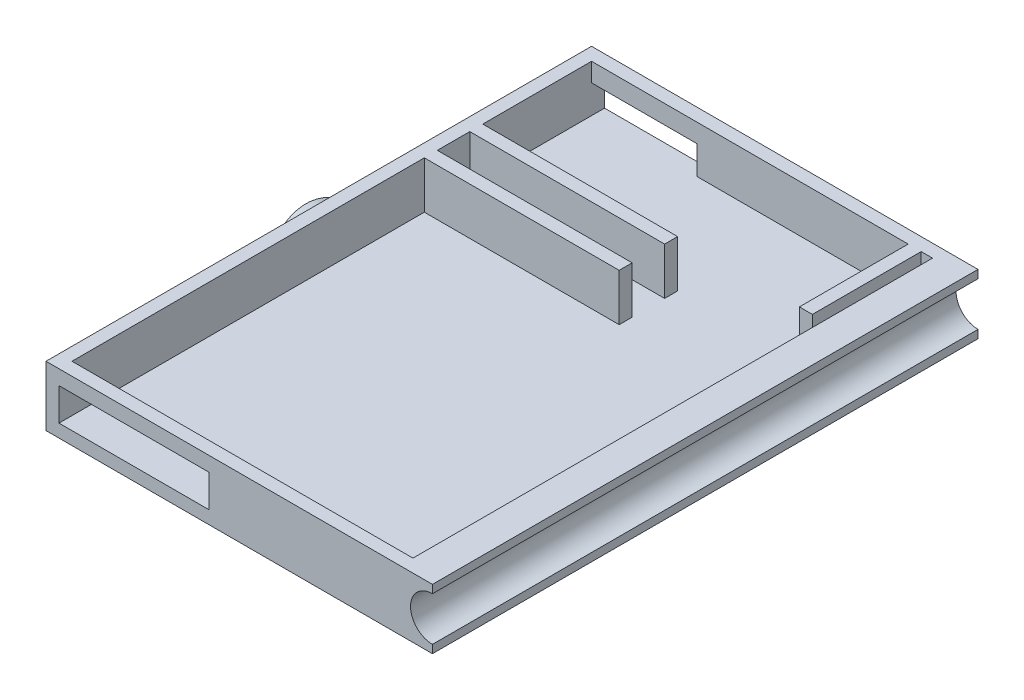
SolidWorks part; units mm, degrees
ref_plane "Front Plane" through (0, 0, 0) normal (0, 0, 1) x (1, 0, 0)
ref_plane "Top Plane" through (0, 0, 0) normal (0, 1, 0) x (1, 0, 0)
ref_plane "Right Plane" through (0, 0, 0) normal (1, 0, 0) x (0, 0, -1)
sketch "Sketch2" plane through (0, 0, 0) normal (0, 1, 0) x (1, 0, 0)
  line L1 (0, 0) -> (42, 0)
  line L2 (0, 0) -> (0, -64)
  line L3 (0, -64) -> (42, -64)
  line L4 (42, 0) -> (42, -64)
  dimension "D1" = 42
  dimension "D2" = 64
extrude "Boss-Extrude1" add sketch "Sketch2" along normal blind 1.6
sketch "Sketch4" plane through (0, 0, 0) normal (0, 1, 0) x (1, 0, 0)
  line L0 (0, 0) -> (0, -64) construction
  line L1 (-1.6, 1.6) -> (46, 1.6)
  line L2 (-1.6, 1.6) -> (-1.6, -65.6)
  line L3 (-1.6, -65.6) -> (46, -65.6)
  line L4 (46, 1.6) -> (46, -65.6)
  line L5 (42, 0) -> (0, 0) construction
  line L6 (42, -64) -> (42, 0) construction
  line L7 (0, -64) -> (42, -64) construction
  line L9 (0, 0) -> (42, 0)
  line L10 (0, 0) -> (0, -64)
  line L11 (0, -64) -> (42, -64)
  line L12 (42, 0) -> (42, -64)
  dimension "D1" = 1.6
  dimension "D2" = 1.6
  dimension "D3" = 4
  dimension "D4" = 1.6
extrude "Boss-Extrude2" add sketch "Sketch4" along normal blind 6.6
sketch "Sketch6" plane through (-1.6, 0, 0) normal (-1, 0, 0) x (0, 0, 1)
  line L0 (-1.6, 0) -> (65.6, 0) construction
  line L1 (25.4, 0) -> (38.6, 0)
  arc A0 (38.6, 0) -> (25.4, 0) centre (32, 0) ccw
extrude "Boss-Extrude3" add sketch "Sketch6" along normal blind 1.6
sketch "Sketch7" plane through (0, 0, 0) normal (0, 0, 1) x (1, 0, 0)
  line L0 (-3.2, 3.3) -> (-3.2, 0)
  line L1 (-3.2, 6.6) -> (-3.2, 0) construction
  line L2 (-3.2, 6.6) -> (-3.2, 3.3)
  line L3 (-3.2, 4.95) -> (-2.7, 4.95)
  line L4 (-2.7, 4.95) -> (-3.2, 6.6)
  line L5 (-3.2, 3.3) -> (-2.7, 3.3)
  line L6 (-2.7, 3.3) -> (-3.2, 4.95)
  line L7 (-3.2, 1.65) -> (-2.7, 1.65)
  line L8 (-2.7, 1.65) -> (-3.2, 3.3)
  line L9 (-3.2, 0) -> (-2.7, 0)
  line L10 (-3.2, 0) -> (-1.6, 0) construction
  line L11 (-2.7, 0) -> (-3.2, 1.65)
  dimension "D1" = 0.5
extrude "Cut-Extrude2" cut sketch "Sketch7" along normal blind 53.6 contours L3 L4 L2 | L5 L6 L2 | L7 L8 L0 | L9 L11 L0
sketch "Sketch12" plane through (0, 0, 64) normal (0, 0, -1) x (-1, 0, 0)
  line L1 (0, 1.6) -> (-18.5, 1.6)
  line L2 (0, 1.6) -> (0, 5.6)
  line L3 (0, 5.6) -> (-18.5, 5.6)
  line L4 (-18.5, 1.6) -> (-18.5, 5.6)
  dimension "D1" = 4
  dimension "D2" = 18.5
extrude "Cut-Extrude5" cut sketch "Sketch12" against normal blind 4.5
sketch "Sketch14" plane through (0, 1.6, 0) normal (0, 1, 0) x (1, 0, 0)
  line L0 (0, 0) -> (0, -65.6) construction
  line L1 (0, -20.6) -> (24, -20.6)
  line L2 (0, -20.6) -> (0, -13.4)
  line L3 (0, -13.4) -> (24, -13.4)
  line L4 (24, -20.6) -> (24, -13.4)
  line L6 (-1.6, -65.6) -> (46, -65.6) construction
  line L7 (42, 0) -> (0, 0) construction
  dimension "D1" = 45
  dimension "D2" = 13.4
  dimension "D3" = 24
extrude "Boss-Extrude6" add sketch "Sketch14" along normal blind 5
sketch "Sketch21" plane through (0, 6.6, 0) normal (0, 1, 0) x (1, 0, 0)
  line L0 (0, -13.4) -> (0, 0)
  line L1 (-1.6, 1.6) -> (46, 1.6)
  line L2 (-1.6, 1.6) -> (-1.6, -65.6)
  line L3 (-1.6, -65.6) -> (46, -65.6)
  line L4 (46, 1.6) -> (46, -65.6)
  line L5 (42, -64) -> (0, -64)
  line L6 (42, -64) -> (42, 0)
  line L7 (42, 0) -> (0, 0)
  line L8 (0, -64) -> (0, -20.6)
  line L9 (0, -13.4) -> (24, -13.4)
  line L11 (0, -20.6) -> (24, -20.6)
  line L12 (24, -13.4) -> (24, -20.6)
extrude "Boss-Extrude8" add sketch "Sketch21" along normal blind 0.8
sketch "Sketch22" plane through (0, 0, 0) normal (0, 0, 1) x (1, 0, 0)
  line L1 (0, 1.6) -> (13, 1.6)
  line L2 (0, 1.6) -> (0, 5.1)
  line L3 (0, 5.1) -> (13, 5.1)
  line L4 (13, 1.6) -> (13, 5.1)
  dimension "D1" = 13
  dimension "D2" = 3.5
extrude "Cut-Extrude6" cut sketch "Sketch22" against normal blind 10.8
sketch "Sketch26" plane through (0, 7.4, 0) normal (0, 1, 0) x (1, 0, 0)
  line L0 (24, -13.4) -> (24, -20.6) construction
  line L1 (24, -15) -> (0, -15)
  line L2 (24, -15) -> (24, -19)
  line L3 (24, -19) -> (0, -19)
  line L4 (0, -15) -> (0, -19)
  line L5 (24, -13.4) -> (0, -13.4) construction
  line L6 (24, -20.6) -> (0, -20.6) construction
  line L7 (-1.6, 1.6) -> (-1.6, -65.6) construction
  dimension "D1" = 1.6
  dimension "D2" = 1.6
  dimension "D3" = 1.6
extrude "Cut-Extrude7" cut sketch "Sketch26" against normal blind 5.8
sketch "Sketch27" plane through (0, 1.6, 0) normal (0, 1, 0) x (1, 0, 0)
  line L1 (42, 0) -> (39, 0)
  line L2 (42, 0) -> (42, -13.4)
  line L3 (42, -13.4) -> (39, -13.4)
  line L4 (39, 0) -> (39, -13.4)
  dimension "D1" = 3
  dimension "D2" = 13.4
extrude "Boss-Extrude9" add sketch "Sketch27" along normal blind 5.8
sketch "Sketch28" plane through (0, 0, 65.6) normal (0, 0, 1) x (1, 0, 0)
  line L0 (46, 7.4) -> (46, 0) construction
  circle A0 centre (46, 3.7) radius 2.7
  dimension "D1" = 5.4
extrude "Cut-Extrude8" cut sketch "Sketch28" against normal blind 70.8
sketch "Sketch29" plane through (-1.6, 0, 0) normal (-1, 0, 0) x (0, 0, 1)
  line L2 (25.4, 0) -> (25.4, 7.4)
  line L3 (-1.6, 7.4) -> (65.6, 7.4) construction
  line L4 (38.6, 0) -> (38.6, 7.4)
  line L6 (25.4, 3.7) -> (21.4, 3.7)
  line L7 (25.4, 3.7) -> (25.4, 7.4)
  line L8 (25.4, 7.4) -> (21.4, 7.4)
  line L9 (21.4, 3.7) -> (21.4, 7.4)
  line L10 (38.6, 3.7) -> (42.6, 3.7)
  line L11 (38.6, 3.7) -> (38.6, 7.4)
  line L12 (38.6, 7.4) -> (42.6, 7.4)
  line L13 (42.6, 3.7) -> (42.6, 7.4)
  line M6 (65.6, 7.4) -> (-1.6, 7.4)
  dimension "D1" = 4
  dimension "D2" = 4
extrude "Boss-Extrude10" add sketch "Sketch29" along normal blind 0.5 contours L9 L6 L2 M6 | L10 L13 L4 M6
sketch "Sketch30" plane through (0, 0, 21.4) normal (0, 0, -1) x (-1, 0, 0)
  line L0 (2.1, 5.55) -> (2.1, 3.7)
  line L1 (2.1, 3.7) -> (2.1, 7.4) construction
  line L2 (1.6, 3.7) -> (2.1, 4.625)
  line L3 (2.1, 4.625) -> (1.6, 7.4)
  line L4 (1.6, 7.4) -> (2.1, 7.4)
  line L5 (2.1, 7.4) -> (2.1, 3.7)
  line L6 (2.1, 3.7) -> (1.6, 3.7)
  line M7 (1.6, 3.7) -> (2.1, 3.7)
  line M8 (2.1, 3.7) -> (2.1, 7.4)
  line M9 (2.1, 7.4) -> (1.6, 7.4)
extrude "Cut-Extrude9" cut sketch "Sketch30" against normal blind 4.5 contours L3 L0 M8 M9 | L2 M7 M8
sketch "Sketch31" plane through (0, 0, 42.6) normal (0, 0, 1) x (1, 0, 0)
  line L0 (-2.1, 3.7) -> (-2.1, 5.55)
  line L1 (-2.1, 3.7) -> (-2.1, 7.4) construction
  line L2 (-2.1, 4.625) -> (-1.6, 7.4)
  line L3 (-1.6, 7.4) -> (-2.1, 7.4)
  line L4 (-2.1, 7.4) -> (-2.1, 3.7)
  line L5 (-2.1, 3.7) -> (-1.6, 3.7)
  line L6 (-1.6, 3.7) -> (-2.1, 4.625)
  line M2 (-1.6, 7.4) -> (-2.1, 7.4)
  line M3 (-2.1, 7.4) -> (-2.1, 3.7)
  line M4 (-2.1, 3.7) -> (-1.6, 3.7)
extrude "Cut-Extrude10" cut sketch "Sketch31" against normal blind 4.5 contours L2 M3 M2 | L6 L0 M4
sketch "Sketch38" plane through (0, 7.4, 0) normal (0, 1, 0) x (1, 0, 0)
  line L0 (39, 0) -> (39, -13.4) construction
  line L1 (42, -13.4) -> (40.6, -13.4)
  line L2 (42, -13.4) -> (42, 0)
  line L3 (42, 0) -> (40.6, 0)
  line L4 (40.6, -13.4) -> (40.6, 0)
  dimension "D1" = 1.6
extrude "Cut-Extrude12" cut sketch "Sketch38" against normal blind 5.8
